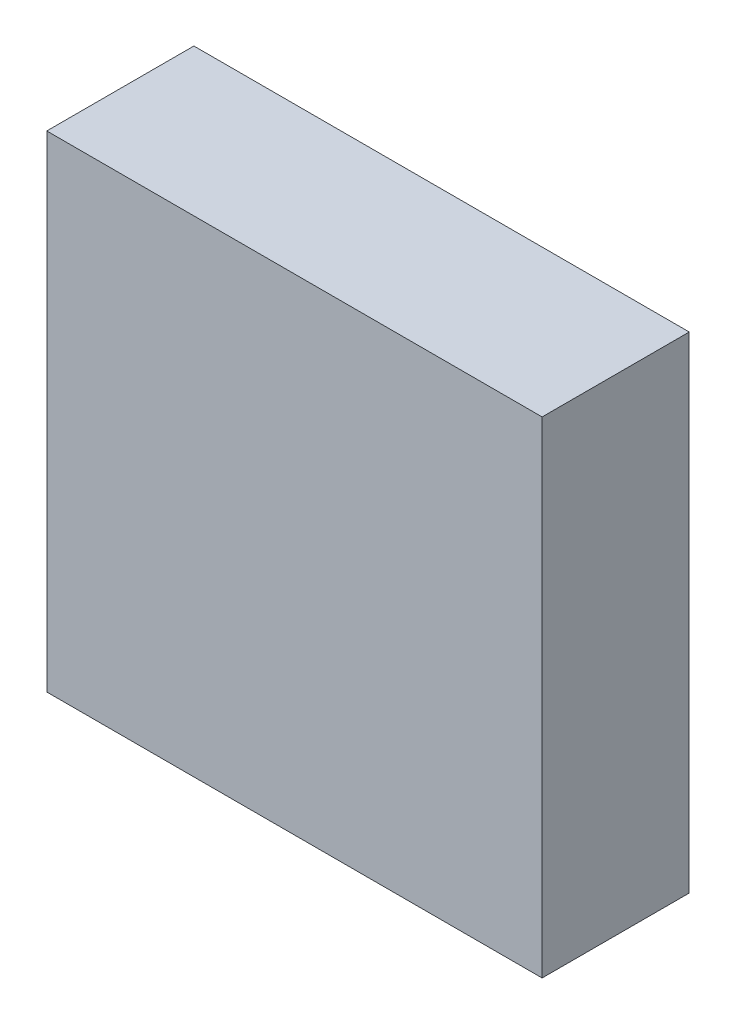
SolidWorks part; units mm, degrees
ref_plane "Front Plane" through (0, 0, 0) normal (0, 0, 1) x (1, 0, 0)
ref_plane "Top Plane" through (0, 0, 0) normal (0, 1, 0) x (1, 0, 0)
ref_plane "Right Plane" through (0, 0, 0) normal (1, 0, 0) x (0, 0, -1)
sketch "Sketch1" plane through (0, 0, 0) normal (0, 0, 1) x (1, 0, 0)
  line L1 (0, 0) -> (36.7, 0)
  line L2 (0, 0) -> (0, 36)
  line L3 (0, 36) -> (36.7, 36)
  line L4 (36.7, 0) -> (36.7, 36)
  dimension "D1" = 36.7
  dimension "D2" = 36
extrude "Boss-Extrude1" add sketch "Sketch1" along normal blind 10.9
